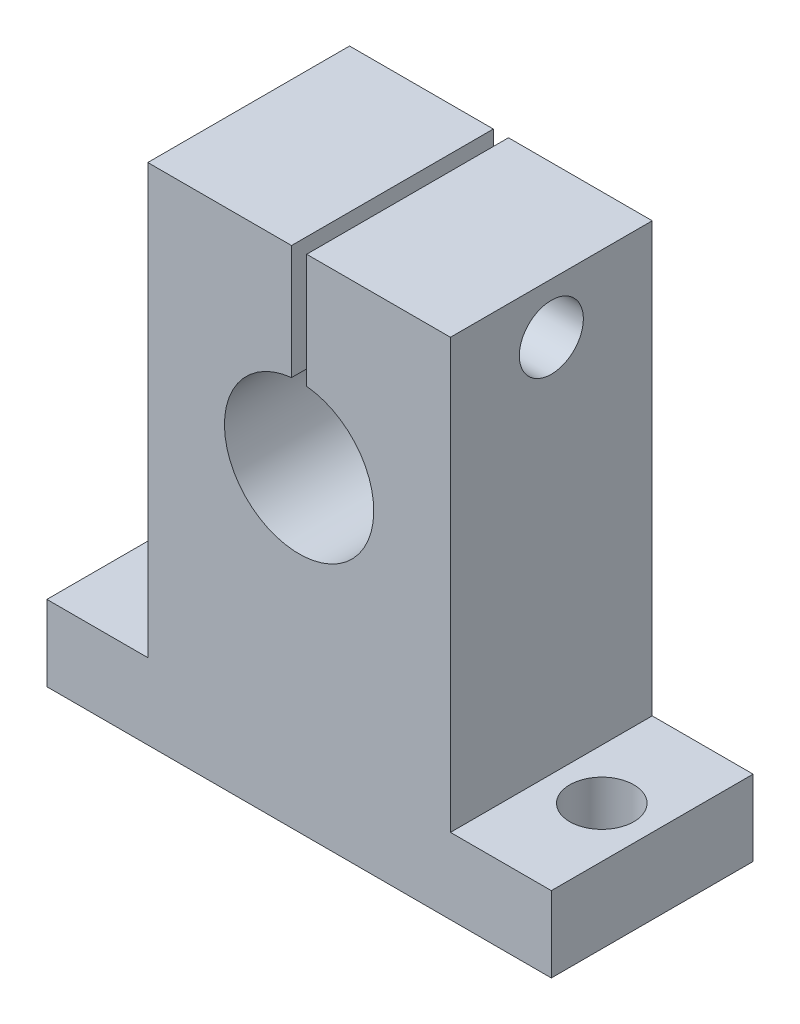
SolidWorks part; units mm, degrees
material "Acero al carbono no aleado"
ref_plane "Alzado" through (0, 0, 0) normal (0, 0, 1) x (1, 0, 0)
ref_plane "Planta" through (0, 0, 0) normal (0, 1, 0) x (1, 0, 0)
ref_plane "Vista lateral" through (0, 0, 0) normal (1, 0, 0) x (0, 0, -1)
sketch "Croquis1" plane through (0, 0, 0) normal (0, 0, 1) x (1, 0, 0)
  line L0 (0, 33.2823) -> (0, -31.3) construction
  line L1 (-15, 18.7) -> (-0.75, 18.7)
  line L6 (-15, 18.7) -> (-15, -23.8)
  line L8 (15, 18.7) -> (15, -23.8)
  line L9 (15, -23.8) -> (25, -23.8)
  line L11 (-0.75, 18.7) -> (-0.75, 7.3619)
  line L13 (0.75, 18.7) -> (0.75, 7.3619)
  line L14 (-25, -23.8) -> (-15, -23.8)
  line L15 (-25, -23.8) -> (-25, -31.3)
  line L16 (-25, -31.3) -> (25, -31.3)
  line L17 (25, -23.8) -> (25, -31.3)
  line L18 (0.75, 18.7) -> (15, 18.7)
  arc A3 (-0.75, 7.3619) -> (0.75, 7.3619) centre (0, 0) ccw
  dimension "D1" = 14.8
  dimension "D2" = 50
  dimension "D3" = 31.3
  dimension "D5" = 14.25
  dimension "D6" = 50
  dimension "D7" = 7.5
  dimension "D8" = 15
extrude "Saliente-Extruir1" add sketch "Croquis1" along normal blind 20
sketch "Croquis2" plane through (0, -23.8, 0) normal (0, 1, 0) x (1, 0, 0)
  line L0 (-20, 0) -> (-20, -20) construction
  line L1 (-15, 0) -> (-25, 0) construction
  line L2 (-15, -20) -> (-25, -20) construction
  line L3 (-25, -10) -> (-15, -10) construction
  line L4 (-25, -20) -> (-25, 0) construction
  line L5 (-15, -20) -> (-15, 0) construction
  line L6 (20, 0) -> (20, -20) construction
  line L7 (25, 0) -> (15, 0) construction
  line L8 (25, -20) -> (15, -20) construction
  line L9 (15, -10) -> (25, -10) construction
  line L10 (15, -20) -> (15, 0) construction
  line L11 (25, -20) -> (25, 0) construction
  circle A0 centre (-20, -10) radius 3.175
  circle A1 centre (20, -10) radius 3.175
  dimension "D1" = 6.35
  dimension "D2" = 6.35
extrude "Cortar-Extruir1" cut sketch "Croquis2" against normal through all
sketch "Croquis3" plane through (15, 0, 0) normal (1, 0, 0) x (0, 0, -1)
  line L0 (-10, 18.7) -> (-10, -23.8) construction
  line L1 (-20, 18.7) -> (0, 18.7) construction
  line L2 (-20, -23.8) -> (0, -23.8) construction
  line L3 (0, 13.7) -> (-20, 13.7) construction
  line L4 (0, -23.8) -> (0, 18.7) construction
  line L5 (-20, -23.8) -> (-20, 18.7) construction
  circle A0 centre (-10, 13.7) radius 3.175
  dimension "D2" = 6.35
  dimension "D1" = 5
extrude "Cortar-Extruir2" cut sketch "Croquis3" against normal through all and the other way through all
